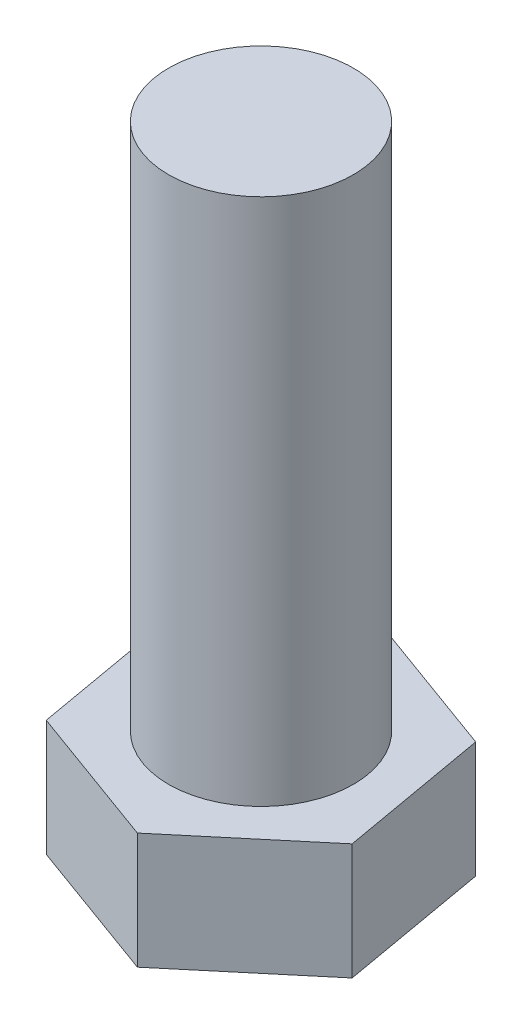
SolidWorks part; units mm, degrees
ref_plane "Спереди" through (0, 0, 0) normal (0, 0, 1) x (1, 0, 0)
ref_plane "Сверху" through (0, 0, 0) normal (0, 1, 0) x (1, 0, 0)
ref_plane "Справа" through (0, 0, 0) normal (1, 0, 0) x (0, 0, -1)
sketch "Эскиз1" plane through (0, 0, 0) normal (0, 1, 0) x (1, 0, 0)
  line L1 (2.0067, -11.3713) -> (10.8512, -3.9478)
  line L2 (10.8512, -3.9478) -> (8.8445, 7.4235)
  line L3 (8.8445, 7.4235) -> (-2.0067, 11.3713)
  line L4 (-2.0067, 11.3713) -> (-10.8512, 3.9478)
  line L5 (-10.8512, 3.9478) -> (-8.8445, -7.4235)
  line L6 (-8.8445, -7.4235) -> (2.0067, -11.3713)
  circle A0 centre (0, 0) radius 10 construction
extrude "Вытянуть1" add sketch "Эскиз1" along normal blind 8.8
sketch "Эскиз3" plane through (0, 8.8, 0) normal (0, 1, 0) x (1, 0, 0)
  circle A0 centre (0, 0) radius 7
extrude "Вытянуть2" add sketch "Эскиз3" along normal blind 40
